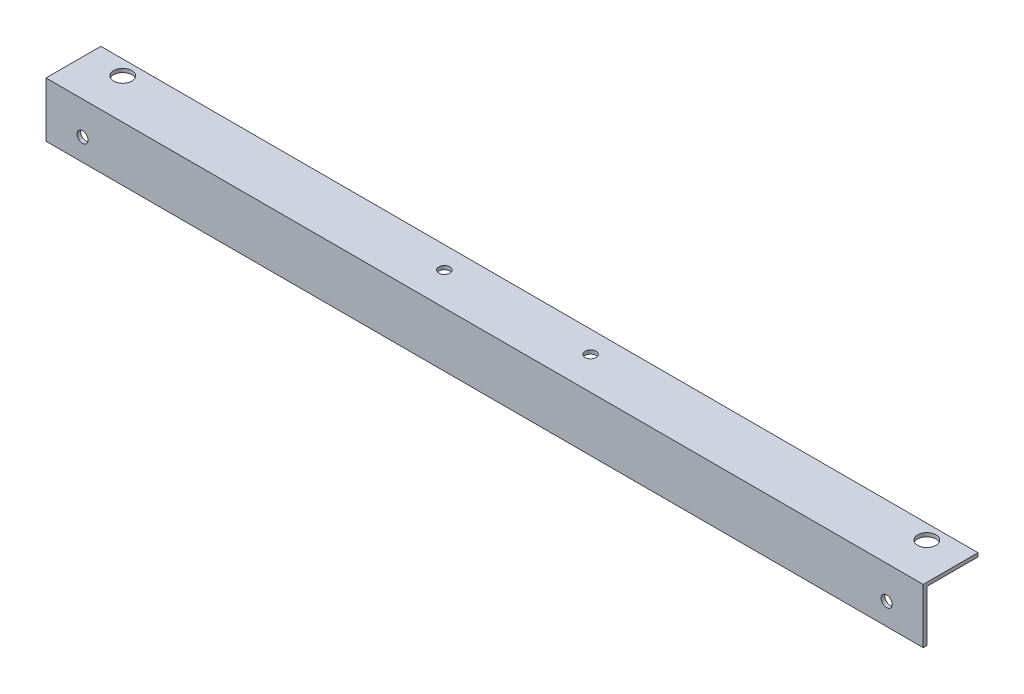
SolidWorks part; units mm, degrees
material "3.3535 (EN-AW 5754)"
ref_plane "Front" through (0, 0, 0) normal (0, 0, 1) x (1, 0, 0)
ref_plane "Top" through (0, 0, 0) normal (0, 1, 0) x (1, 0, 0)
ref_plane "Right" through (0, 0, 0) normal (1, 0, 0) x (0, 0, -1)
sketch "Esquisse1" plane through (0, 0, 0) normal (1, 0, 0) x (0, 0, -1)
  line L0 (0, -15) -> (0, 0)
  line L1 (0, 0) -> (15, 0)
  dimension "D1" = 15
extrude "Extru.-Mince1" add sketch "Esquisse1" along normal mid plane 240 thin
sketch "Esquisse2" plane through (0, 0, 0) normal (0, 0, 1) x (1, 0, 0)
  line L0 (0, -50) -> (0, 50) construction
  line L1 (120, -15) -> (-120, -15) construction
  circle A0 centre (-110, -9) radius 1.5
  circle A1 centre (110, -9) radius 1.5
  dimension "D1" = 220
  dimension "D2" = 3
  dimension "D3" = 6
extrude "Enlèv. mat.-Extru.1" cut sketch "Esquisse2" against normal blind 3
sketch "Esquisse3" plane through (0, 0, 0) normal (0, 1, 0) x (1, 0, 0)
  line L0 (0, -50) -> (0, 50) construction
  line L1 (120, 1) -> (-120, 1) construction
  circle A0 centre (-110, 11) radius 2.5
  circle A1 centre (-20, 9) radius 1.5
  circle A2 centre (110, 11) radius 2.5
  circle A3 centre (20, 9) radius 1.5
  point P4 (-15.4102, 9)
  dimension "D1" = 10
  dimension "D2" = 5
  dimension "D3" = 220
  dimension "D4" = 8
  dimension "D5" = 3
  dimension "D6" = 40
extrude "Enlèv. mat.-Extru.2" cut sketch "Esquisse3" against normal blind 3
